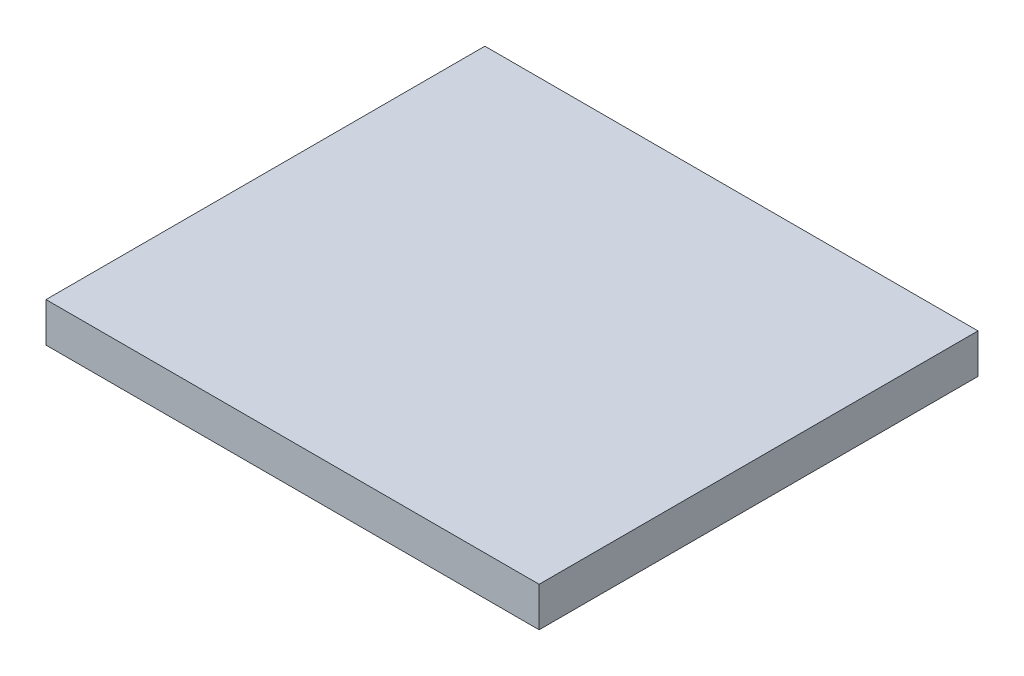
SolidWorks part; units mm, degrees
material "ABS"
ref_plane "前视基准面" through (0, 0, 0) normal (0, 0, 1) x (1, 0, 0)
ref_plane "上视基准面" through (0, 0, 0) normal (0, 1, 0) x (1, 0, 0)
ref_plane "右视基准面" through (0, 0, 0) normal (1, 0, 0) x (0, 0, -1)
other "Configuration Table"
sketch "草图1" plane through (0, 0, 0) normal (0, 1, 0) x (1, 0, 0)
  line L0 (0, 0) -> (0, -44.5)
  line L1 (0, -44.5) -> (50, -44.5)
  line L2 (50, -44.5) -> (50, 0)
  line L3 (50, 0) -> (0, 0)
  dimension "D1" = 50
  dimension "D2" = 44.5
extrude "凸台-拉伸1" add sketch "草图1" along normal blind 4
